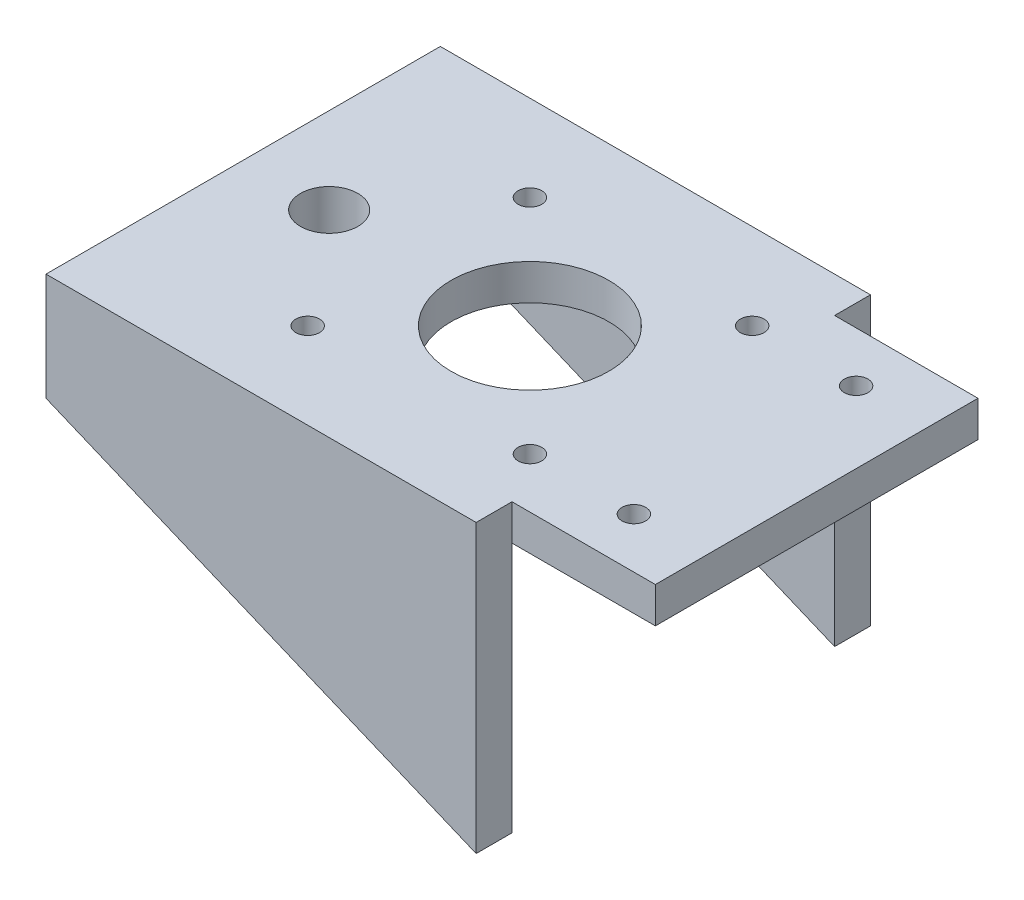
SolidWorks part; units mm, degrees
ref_plane "前视基准面" through (0, 0, 0) normal (0, 0, 1) x (1, 0, 0)
ref_plane "上视基准面" through (0, 0, 0) normal (0, 1, 0) x (1, 0, 0)
ref_plane "右视基准面" through (0, 0, 0) normal (1, 0, 0) x (0, 0, -1)
sketch "草图1" plane through (0, 0, 0) normal (0, 1, 0) x (1, 0, 0)
  line L5 (-40, 22.5) -> (40, 22.5)
  line L6 (-40, 22.5) -> (-40, -22.5)
  line L7 (-40, -22.5) -> (40, -22.5)
  line L8 (40, 22.5) -> (40, -22.5)
  line L13 (0, -22.5) -> (0, 22.5) construction
  line L14 (-40, 0) -> (40, 0) construction
  point P0 (0, 0)
  dimension "D1" = 80
  dimension "D2" = 45
extrude "凸台-拉伸1" add sketch "草图1" along normal blind 5
sketch "草图2" plane through (0, 5, 0) normal (0, 1, 0) x (1, 0, 0)
  line L15 (-40, 0) -> (40, 0) construction
  line L16 (-40, 22.5) -> (-40, -22.5) construction
  line L17 (40, -22.5) -> (40, 22.5) construction
  line L18 (0, 22.5) -> (0, -22.5) construction
  line L19 (40, 22.5) -> (-40, 22.5) construction
  line L20 (-40, -22.5) -> (40, -22.5) construction
  line L21 (30, 22.5) -> (30, -22.5) construction
  line L22 (20, 22.5) -> (20, -22.5) construction
  line L24 (-15.5, 15.5) -> (15.5, 15.5) construction
  line L25 (-15.5, 15.5) -> (-15.5, -15.5) construction
  line L26 (-15.5, -15.5) -> (15.5, -15.5) construction
  line L27 (15.5, 15.5) -> (15.5, -15.5) construction
  line L28 (0, -15.5) -> (0, 15.5) construction
  line L29 (-15.5, 0) -> (15.5, 0) construction
  circle A0 centre (-15.5, 15.5) radius 1.65
  circle A1 centre (15.5, 15.5) radius 1.65
  circle A2 centre (15.5, -15.5) radius 1.65
  circle A3 centre (-15.5, -15.5) radius 1.65
  circle A4 centre (30, 15.5) radius 1.65
  circle A6 centre (30, -15.5) radius 1.65
  circle A7 centre (-28, 0) radius 4
  circle A8 centre (0, 0) radius 11
  point P36 (0, 0)
  dimension "D3" = 3.3
  dimension "D4" = 8
  dimension "D5" = 22
  dimension "D1" = 10
  dimension "D2" = 10
  dimension "D6" = 31
  dimension "D7" = 28
extrude "切除-拉伸1" cut sketch "草图2" against normal through all
sketch "草图3" plane through (0, 0, 0) normal (0, -1, 0) x (1, 0, 0)
  circle A0 centre (-28, 0) radius 7.5
  circle A1 centre (-28, 0) radius 4 construction
  circle A2 centre (-28, 0) radius 4
  dimension "D1" = 15
extrude "凸台-拉伸2" add sketch "草图3" along normal blind 10
sketch "草图6" plane through (0, 0, 22.5) normal (0, 0, 1) x (1, 0, 0)
  line L0 (-40, 5) -> (-40, -10)
  line L1 (-40, -10) -> (20, -35)
  line L2 (20, -35) -> (20, 5)
  line L3 (-40, 5) -> (40, 5) construction
  line L4 (20, 5) -> (-40, 5)
  line L5 (40, 5) -> (40, 0) construction
  dimension "D1" = 20
  dimension "D2" = 40
  dimension "D3" = 15
extrude "凸台-拉伸4" add sketch "草图6" along normal blind 5
ref_plane "基准面1" through (0, 0, 0) normal (0, 0, -1) x (-1, 0, 0)
mirror "镜向1" about plane through (0, 0, 0) normal (0, 0, -1) of "凸台-拉伸4"
